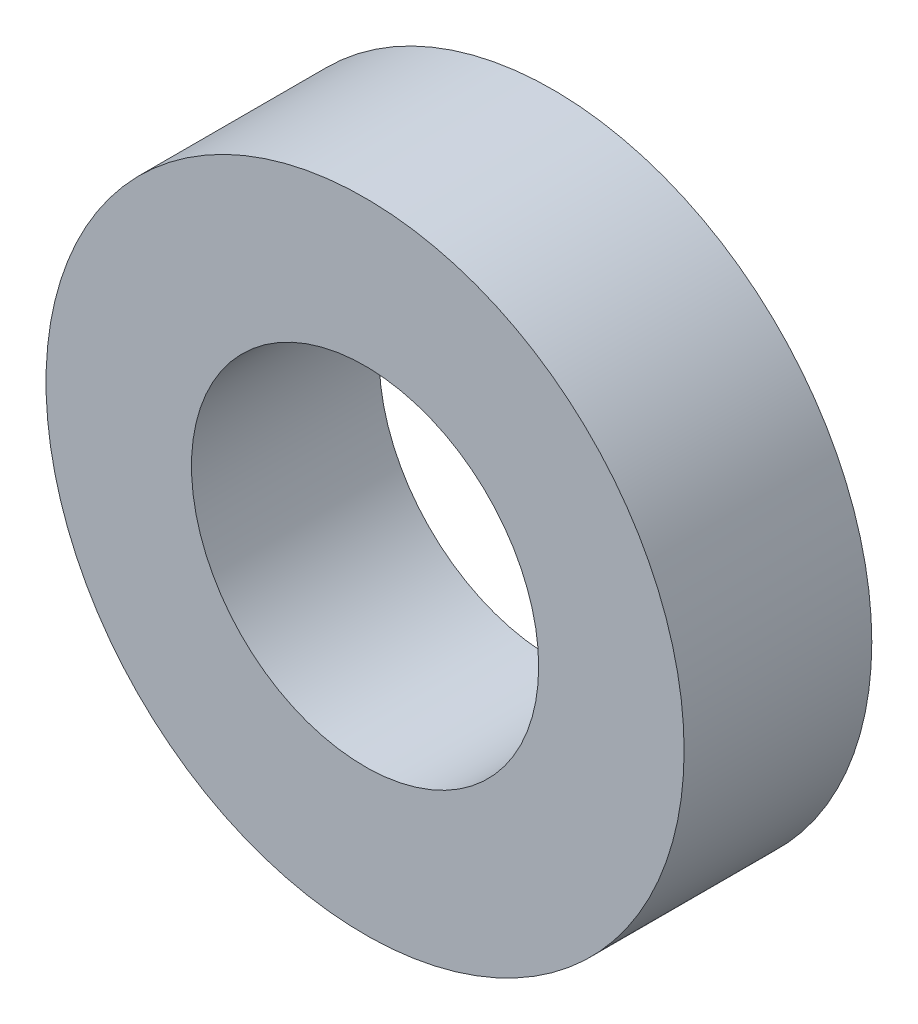
SolidWorks part; units mm, degrees
ref_plane "Front Plane" through (0, 0, 0) normal (0, 0, 1) x (1, 0, 0)
ref_plane "Top Plane" through (0, 0, 0) normal (0, 1, 0) x (1, 0, 0)
ref_plane "Right Plane" through (0, 0, 0) normal (1, 0, 0) x (0, 0, -1)
sketch "Эскиз2" plane through (0, 0, 0) normal (0, 0, 1) x (1, 0, 0)
  circle A0 centre (0, 0) radius 6.8
  circle A1 centre (0, 0) radius 3.7
  dimension "D1" = 13.6
  dimension "D2" = 7.4
extrude "Бобышка-Вытянуть1" add sketch "Эскиз2" along normal mid plane 4
